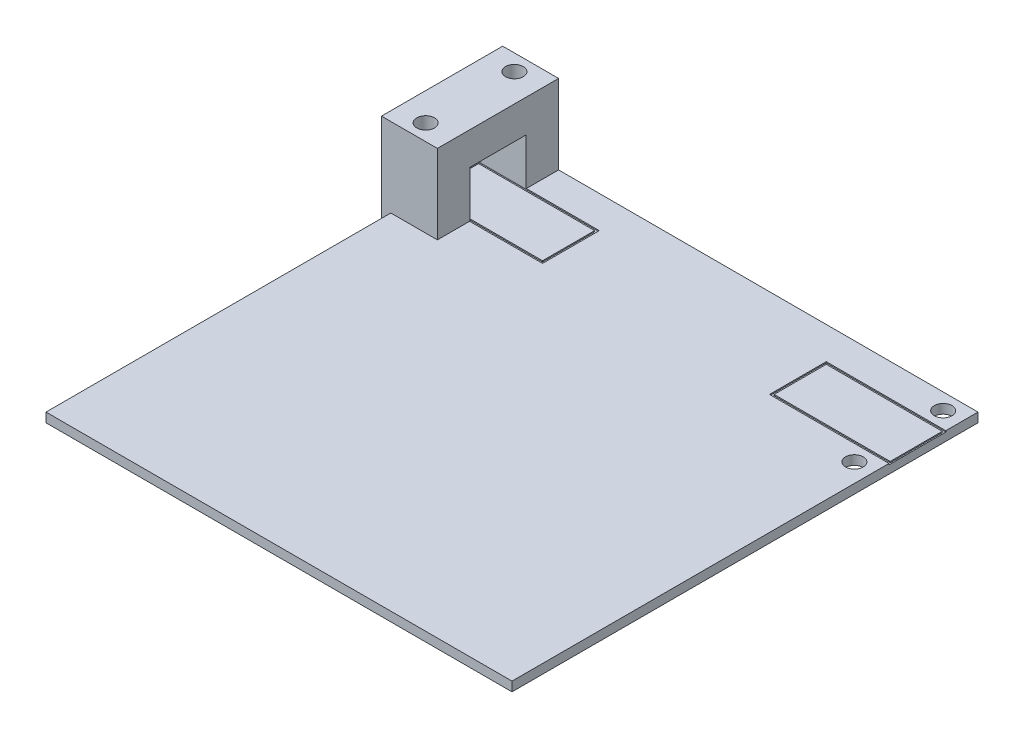
SolidWorks part; units mm, degrees
ref_plane "Front" through (0, 0, 0) normal (0, 0, 1) x (1, 0, 0)
ref_plane "Top" through (0, 0, 0) normal (0, 1, 0) x (1, 0, 0)
ref_plane "Right" through (0, 0, 0) normal (1, 0, 0) x (0, 0, -1)
sketch "Sketch1" plane through (0, 0, 0) normal (0, 1, 0) x (1, 0, 0)
  line L1 (-50, -50) -> (50, -50)
  line L2 (-50, -50) -> (-50, 50)
  line L3 (-50, 50) -> (50, 50)
  line L4 (50, -50) -> (50, 50)
  line L5 (-50, -50) -> (50, 50) construction
  line L6 (-50, 50) -> (50, -50) construction
  point P0 (0, 0)
  dimension "D1" = 100
  dimension "D2" = 100
extrude "Boss-Extrude1" add sketch "Sketch1" along normal blind 2
sketch "Sketch2" plane through (0, 2, 0) normal (0, 1, 0) x (1, 0, 0)
  line L0 (-50, 42.837) -> (-50, 31.153)
  line L1 (-50, 42.837) -> (-24.6, 42.837)
  line L2 (-50, 31.153) -> (-24.6, 31.153)
  line L3 (-24.6, 42.837) -> (-24.6, 31.153)
  line L4 (-50, 50) -> (-50, -50) construction
  line L5 (-50, -50) -> (50, -50) construction
  line L6 (-46, 27.47) -> (-46, 46.52) construction
  circle A0 centre (-46, 46.52) radius 1.5875
  circle A1 centre (-46, 27.47) radius 1.5875
  point P10 (-46, 36.995)
  point P13 (-50, 36.995)
  dimension "D3" = 4
  dimension "D1" = 25.4
  dimension "D2" = 11.684
  dimension "D4" = 96.52
  dimension "D5" = 77.47
hole_wizard "#6 Clearance Hole1" positions "Sketch3" profile "Sketch4" hole size "#6" standard "ANSI Inch" end condition through all
sketch "Sketch3" plane through (0, 2, 0) normal (0, 1, 0) x (1, 0, 0)
  point P0 (-46, 27.47)
  point P3 (-46, 46.52)
sketch "Sketch4" plane through (-46, 2, -27.47) normal (1, 0, 0) x (0, 0, 1)
  line L0 (0, 0) -> (0, 2)
  line L1 (0, 2) -> (1.8986, 2)
  line L2 (1.8986, 2) -> (1.8986, 0)
  line L5 (1.8986, 0) -> (0, 0)
  line L11 (0, -6.35) -> (0, 107.95) construction
  dimension "Thru Hole Dia." = 3.7973
  dimension "Thru Hole Depth" = 2
sketch "Sketch5" plane through (0, 2, 0) normal (0, 1, 0) x (1, 0, 0)
  line L8 (-50.25, 43.087) -> (-50.25, 30.903)
  line L9 (-50.25, 30.903) -> (-24.35, 30.903)
  line L10 (-24.35, 30.903) -> (-24.35, 43.087)
  line L11 (-24.35, 43.087) -> (-50.25, 43.087)
  line L12 (-50.25, 43.087) -> (-50.25, 30.903)
  line L13 (-50.25, 30.903) -> (-24.35, 30.903)
  line L14 (-24.35, 30.903) -> (-24.35, 43.087)
  line L15 (-24.35, 43.087) -> (-50.25, 43.087)
  line L16 (-49.75, 42.587) -> (-49.75, 31.403)
  line L17 (-49.75, 31.403) -> (-24.85, 31.403)
  line L18 (-24.85, 31.403) -> (-24.85, 42.587)
  line L19 (-24.85, 42.587) -> (-49.75, 42.587)
  line L20 (-49.75, 42.587) -> (-49.75, 31.403)
  line L21 (-49.75, 31.403) -> (-24.85, 31.403)
  line L22 (-24.85, 31.403) -> (-24.85, 42.587)
  line L23 (-24.85, 42.587) -> (-49.75, 42.587)
  dimension "D1" = 0.25
  dimension "D2" = 0.25
extrude "Cut-Extrude1" cut sketch "Sketch5" against normal blind 0.25
mirror "Mirror1" about plane through (0, 0, 0) normal (1, 0, 0) of "#6 Clearance Hole1", "Cut-Extrude1"
sketch "Sketch6" plane through (-50, 0, 0) normal (-1, 0, 0) x (0, 0, 1)
  line L0 (-36.995, 0.045) -> (-36.995, -7.6268) construction
  line L2 (-50, 2) -> (-50, 0) construction
  line L3 (-30.995, 12) -> (-42.995, 12)
  line L4 (-30.995, 12) -> (-30.995, 2)
  line L6 (-42.995, 12) -> (-42.995, 2)
  line L7 (-50, 2) -> (-42.995, 2)
  line L9 (-43.087, 1.75) -> (-30.903, 1.75) construction
  line L10 (-50, 2) -> (-50, 19.005)
  line L11 (-50, 19.005) -> (-23.99, 19.005)
  line L12 (-23.99, 19.005) -> (-23.99, 2)
  line L13 (-30.903, 2) -> (50, 2) construction
  line L14 (-23.99, 2) -> (-30.995, 2)
  line L15 (-42.995, 12) -> (-50, 12) construction
  line L16 (-42.995, 12) -> (-42.995, 19.005) construction
  line L17 (-42.995, 19.005) -> (-50, 19.005) construction
  line L18 (-50, 12) -> (-50, 19.005) construction
  line L19 (-30.995, 12) -> (-23.99, 12) construction
  line L20 (-30.995, 12) -> (-30.995, 19.005) construction
  line L21 (-30.995, 19.005) -> (-23.99, 19.005) construction
  line L22 (-23.99, 12) -> (-23.99, 19.005) construction
  point P1 (-36.995, 7)
  point P11 (-36.995, 1.75)
  point P22 (-36.995, 12)
  dimension "D1" = 10
  dimension "D2" = 12
extrude "Boss-Extrude2" add sketch "Sketch6" against normal blind 10 separate body
sketch "Sketch9" plane through (0, 2, 0) normal (0, -1, 0) x (1, 0, 0)
  circle A0 centre (-46, -27.47) radius 1.8986 construction
  circle A1 centre (-46, -46.52) radius 1.8986 construction
  circle A2 centre (-46, -27.47) radius 1.8986
  circle A3 centre (-46, -46.52) radius 1.8986
extrude "Cut-Extrude2" cut sketch "Sketch9" against normal through all
sketch "Sketch12" plane through (-50, 0, 0) normal (-1, 0, 0) x (0, 0, 1)
  line L0 (-23.99, 2) -> (-23.99, 19.005) construction
  line L1 (-23.99, 19.005) -> (-50, 19.005) construction
  line L2 (-50, 19.005) -> (-50, 2) construction
  line L3 (-23.99, 2) -> (-23.99, 19.005)
  line L4 (-23.99, 19.005) -> (-50, 19.005)
  line L5 (-50, 19.005) -> (-50, 2)
  line L6 (-50, 2) -> (-50, 0)
  line L7 (-50, 0) -> (-23.99, 0)
  line L9 (-23.99, 2) -> (-23.99, 0)
  line L10 (-50, 0) -> (50, 0) construction
  line L11 (-30.995, 7) -> (-42.995, 7) construction
  line L12 (-30.995, 12) -> (-30.995, 2) construction
  line L13 (-42.995, 2) -> (-42.995, 12) construction
  line L14 (-36.995, 7) -> (-36.995, 8.8293) construction
  circle A1 centre (-41.495, 7) radius 0.8
  circle A2 centre (-32.495, 7) radius 0.8
  circle A3 centre (-36.995, 7) radius 2.5097
  point P15 (-36.995, 7)
  dimension "D1" = 1.6
  dimension "D2" = 4.5
extrude "Boss-Extrude3" add sketch "Sketch12" along normal blind 2
ref_plane "Plane1" through (0, 0, -36.995) normal (0, 0, -1) x (-1, 0, 0)
ref_plane "Plane2" through (0, 6, 0) normal (0, 1, 0) x (1, 0, 0)
ref_plane "Plane3" through (-27, 0, 0) normal (1, 0, 0) x (0, 0, -1)
